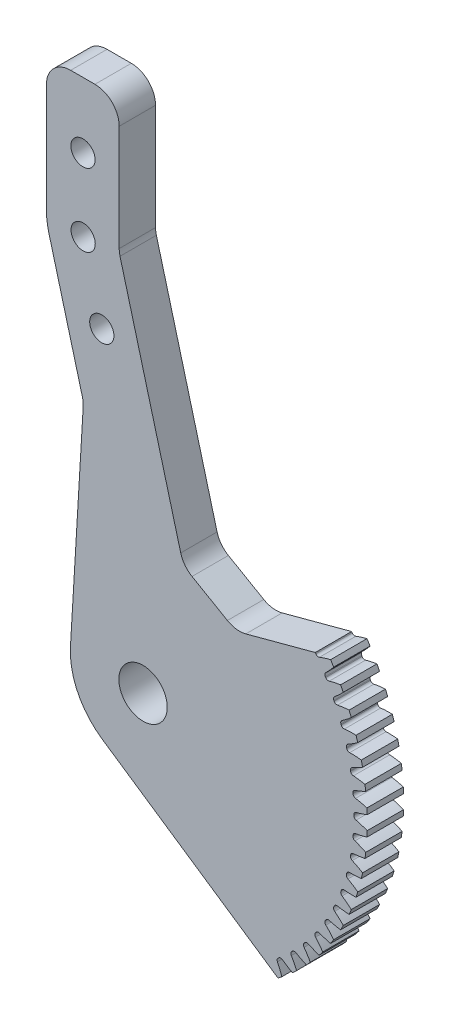
SolidWorks part; units mm, degrees
material "Delrin 2700 NC010, Low Viscosity Acetal Copolymer (SS)"
ref_plane "Front Plane" through (0, 0, 0) normal (0, 0, 1) x (1, 0, 0)
ref_plane "Top Plane" through (0, 0, 0) normal (0, 1, 0) x (1, 0, 0)
ref_plane "Right Plane" through (0, 0, 0) normal (1, 0, 0) x (0, 0, -1)
sketch "Sketch2" plane through (0, 0, 0) normal (0, 0, 1) x (1, 0, 0)
  circle A0 centre (0, 0) radius 60.325
  dimension "D1" = 120.65
extrude "Boss-Extrude2" add sketch "Sketch2" along normal mid plane 9.525
sketch "Sketch3" plane through (0, 0, 4.7625) normal (0, 0, 1) x (1, 0, 0)
  line L0 (0, 0) -> (-57.8242, 215.8028) construction
  line L1 (0, 0) -> (60.325, 0) construction
  line L2 (-15.6133, 58.2695) -> (-24.6525, 92.0044)
  line L3 (-24.6525, 92.0044) -> (-6.2516, 96.9349)
  line L4 (-6.2516, 96.9349) -> (3.5866, 60.2183)
  circle A0 centre (0, 0) radius 60.325 construction
  arc A1 (3.5866, 60.2183) -> (-15.6133, 58.2695) centre (0, 0) ccw
  point P9 (0, 0)
  point P11 (0, 0)
  point P12 (0, 0)
  dimension "D1" = 105
  dimension "D2" = 19.05
  dimension "D3" = 95.25
extrude "Boss-Extrude3" add sketch "Sketch3" against normal up to surface (9.525 mm away) up to face at (60.325, 0, -4.7625)
sketch "Sketch4" plane through (0, 0, 4.7625) normal (0, 0, 1) x (1, 0, 0)
  line L0 (-6.2516, 96.9349) -> (-25.3016, 96.9349)
  line L1 (-25.3016, 96.9349) -> (-25.3016, 131.8599)
  line L2 (-25.3016, 131.8599) -> (-6.2516, 131.8599)
  line L3 (-6.2516, 131.8599) -> (-6.2516, 96.9349)
  line L4 (3.5866, 60.2183) -> (-6.2516, 96.9349) construction
  dimension "D3" = 34.925
  dimension "D1" = 19.05
  dimension "D2" = 165
extrude "Boss-Extrude4" add sketch "Sketch4" against normal up to surface (9.525 mm away) separate body
sketch "Sketch5" plane through (0, 0, 4.7625) normal (0, 0, 1) x (1, 0, 0)
  line L0 (-25.3016, 96.9349) -> (-6.2516, 96.9349) construction
  line L1 (-6.2516, 96.9349) -> (-24.6525, 92.0044) construction
  line L2 (-25.3016, 96.9349) -> (-6.2516, 96.9349)
  line L3 (-6.2516, 96.9349) -> (-24.6525, 92.0044)
  arc A0 (-25.3016, 96.9349) -> (-24.6525, 92.0044) centre (-6.2516, 96.9349) ccw
extrude "Boss-Extrude5" add sketch "Sketch5" against normal up to surface (9.525 mm away)
hole_wizard "1/2 (0.5) Diameter Hole1" positions "Sketch6" profile "Sketch7" hole size "1/2" standard "ANSI Inch" end condition through all
sketch "Sketch6" plane through (0, 0, 4.7625) normal (0, 0, 1) x (1, 0, 0)
  point P0 (0, 0)
sketch "Sketch7" plane through (0, 0, 4.7625) normal (1, 0, 0) x (0, -1, 0)
  line L0 (0, 0) -> (0, 9.525)
  line L1 (0, 9.525) -> (6.3373, 9.525)
  line L2 (6.3373, 9.525) -> (6.3373, 0)
  line L5 (6.3373, 0) -> (0, 0)
  line L11 (0, -6.35) -> (0, 107.95) construction
  dimension "Thru Hole Dia." = 12.6746
  dimension "Thru Hole Depth" = 9.525
sketch "Sketch8" plane through (0, 0, 4.7625) normal (0, 0, 1) x (1, 0, 0)
  line L0 (0, 0) -> (58.2695, 15.6133) construction
  line L1 (-24.6525, 92.0044) -> (-15.6133, 58.2695) construction
  line L2 (24.377, 26.2538) -> (50.3573, 33.2152)
  line L3 (24.377, 26.2538) -> (10.548, 34.2381)
  line L4 (3.5866, 60.2183) -> (10.548, 34.2381)
  line L5 (3.5866, 60.2183) -> (-6.2516, 96.9349) construction
  line L7 (-4.9305, 18.4009) -> (53.339, 34.0141) construction
  arc A0 (-15.6133, 58.2695) -> (3.5866, 60.2183) centre (0, 0) ccw construction
  arc A1 (50.3573, 33.2152) -> (3.5866, 60.2183) centre (0, 0) ccw
  dimension "D2" = 45
  dimension "D3" = 34.925
  dimension "D1" = 19.05
extrude "Cut-Extrude1" cut sketch "Sketch8" against normal through all
sketch "Sketch9" plane through (0, 0, 4.7625) normal (0, 0, 1) x (1, 0, 0)
  line L0 (-15.6133, 58.2695) -> (-19.0163, 1.1326)
  line L1 (0, 0) -> (58.2695, 15.6133) construction
  line L2 (-24.6525, 92.0044) -> (-15.6133, 58.2695) construction
  line L3 (0, 0) -> (36.7235, -47.859) construction
  line L4 (36.7235, -47.859) -> (-10.6778, -15.7761)
  arc A0 (-19.0163, 1.1326) -> (-10.6778, -15.7761) centre (0, 0) ccw
  arc A1 (-15.6133, 58.2695) -> (50.3573, 33.2152) centre (0, 0) ccw construction
  arc A2 (-15.6133, 58.2695) -> (36.7235, -47.859) centre (0, 0) ccw
  dimension "D1" = 38.1
  dimension "D2" = 67.5
extrude "Cut-Extrude2" cut sketch "Sketch9" against normal through all
sketch "Sketch10" plane through (0, 0, 4.7625) normal (0, 0, 1) x (1, 0, 0)
  line L0 (0, 0) -> (60.325, 0) construction
  line L1 (58.6816, -2.5621) -> (0, 0) construction
  circle A0 centre (0, 0) radius 6.3373 construction
  arc A1 (36.7235, -47.859) -> (50.3573, 33.2152) centre (0, 0) ccw construction
  line B0 (23.419, -49.9795) -> (23.233, -50.0662)
  line B1 (18.9739, -51.8304) -> (18.7811, -51.9006)
  line B2 (14.3844, -53.2869) -> (14.1862, -53.34)
  line B3 (13.4521, -57.1763) -> (12.7131, -57.3452)
  line B4 (12.7131, -57.3452) -> (13.7439, -61.9948)
  line B5 (46.8171, 42.9) -> (43.3058, 39.6825)
  line B6 (43.3058, 39.6825) -> (43.8143, 39.1203)
  line B7 (42.2152, 35.5567) -> (42.3471, 35.3995)
  line B8 (45.1535, 31.7421) -> (45.2712, 31.574)
  line B9 (47.7482, 27.6859) -> (47.8508, 27.5082)
  line B10 (49.9795, 23.419) -> (50.0662, 23.233)
  line B11 (51.8304, 18.9739) -> (51.9006, 18.7811)
  line B12 (53.2869, 14.3844) -> (53.34, 14.1862)
  line B13 (54.3378, 9.6854) -> (54.3734, 9.4833)
  line B14 (54.9751, 4.9127) -> (54.993, 4.7083)
  line B15 (55.1941, 0.1026) -> (55.1941, -0.1026)
  line B16 (54.993, -4.7083) -> (54.9751, -4.9127)
  line B17 (54.3734, -9.4833) -> (54.3378, -9.6854)
  line B18 (53.34, -14.1862) -> (53.2869, -14.3844)
  line B19 (51.9006, -18.7811) -> (51.8304, -18.9739)
  line B20 (50.0662, -23.233) -> (49.9795, -23.419)
  line B21 (47.8508, -27.5082) -> (47.7482, -27.6859)
  line B22 (45.2712, -31.574) -> (45.1535, -31.7421)
  line B23 (42.3471, -35.3995) -> (42.2152, -35.5567)
  line B24 (39.1007, -38.9556) -> (38.9556, -39.1007)
  line B25 (35.5567, -42.2152) -> (35.3995, -42.3471)
  line B26 (31.7421, -45.1535) -> (31.574, -45.2712)
  line B27 (27.6859, -47.7482) -> (27.5082, -47.8508)
  circle B28 centre (0, 0) radius 7.9375 construction
  arc B29 (26.4473, -52.4465) -> (27.7921, -51.7464) centre (0, 0) ccw
  arc B30 (24.374, -50.2004) -> (26.4473, -52.4465) centre (42.0357, -35.9774) ccw
  arc B31 (24.374, -50.2004) -> (23.419, -49.9795) centre (23.7558, -50.6982) ccw
  arc B32 (23.233, -50.0662) -> (22.7884, -50.9398) centre (23.5672, -50.7862) ccw
  arc B33 (23.1763, -53.9718) -> (22.7884, -50.9398) centre (0.5402, -55.327) ccw
  arc B34 (21.7757, -54.5519) -> (23.1763, -53.9718) centre (0, 0) ccw
  arc B35 (19.906, -52.1337) -> (21.7757, -54.5519) centre (38.7401, -39.5041) ccw
  arc B36 (19.906, -52.1337) -> (18.9739, -51.8304) centre (19.2468, -52.5758) ccw
  arc B37 (18.7811, -51.9006) -> (18.262, -52.7321) centre (19.0512, -52.647) ccw
  arc B38 (18.3842, -55.7863) -> (18.262, -52.7321) centre (-4.2839, -55.1635) ccw
  arc B39 (16.9383, -56.2422) -> (18.3842, -55.7863) centre (0, 0) ccw
  arc B40 (15.2865, -53.6702) -> (16.9383, -56.2422) centre (35.1497, -42.7302) ccw
  arc B41 (15.2865, -53.6702) -> (14.3844, -53.2869) centre (14.5913, -54.0532) ccw
  arc B42 (14.1862, -53.34) -> (13.5966, -54.1231) centre (14.3902, -54.1071) ccw
  arc B43 (13.4521, -57.1763) -> (13.5966, -54.1231) centre (-9.0754, -54.5803) ccw
  arc B44 (13.7439, -61.9948) -> (46.8171, 42.9) centre (0, 0) ccw
  arc B45 (42.1814, 36.5363) -> (43.8143, 39.1203) centre (23.8718, 49.915) ccw
  arc B46 (42.1814, 36.5363) -> (42.2152, 35.5567) centre (42.8223, 36.068) ccw
  arc B47 (42.3471, 35.3995) -> (43.306, 35.1961) centre (42.9561, 35.9086) ccw
  arc B48 (46.1343, 36.3555) -> (43.306, 35.1961) centre (53.302, 14.8415) ccw
  arc B49 (47.0572, 35.1528) -> (46.1343, 36.3555) centre (0, 0) ccw
  arc B50 (45.2052, 32.7209) -> (47.0572, 35.1528) centre (28.1314, 47.6445) ccw
  arc B51 (45.2052, 32.7209) -> (45.1535, 31.7421) centre (45.8029, 32.1986) ccw
  arc B52 (45.2712, 31.574) -> (46.2087, 31.2878) centre (45.9223, 32.0281) ccw
  arc B53 (49.1273, 32.1963) -> (46.2087, 31.2878) centre (54.3926, 10.1395) ccw
  arc B54 (49.9419, 30.9177) -> (49.1273, 32.1963) centre (0, 0) ccw
  arc B55 (47.885, 28.6565) -> (49.9419, 30.9177) centre (32.1768, 45.0114) ccw
  arc B56 (47.885, 28.6565) -> (47.7482, 27.6859) centre (48.4349, 28.0841) ccw
  arc B57 (47.8508, 27.5082) -> (48.7598, 27.1414) centre (48.5389, 27.9038) ccw
  arc B58 (51.7464, 27.7921) -> (48.7598, 27.1414) centre (55.0694, 5.3602) ccw
  arc B59 (52.4465, 26.4473) -> (51.7464, 27.7921) centre (0, 0) ccw
  arc B60 (50.2004, 24.374) -> (52.4465, 26.4473) centre (35.9774, 42.0357) ccw
  arc B61 (50.2004, 24.374) -> (49.9795, 23.419) centre (50.6982, 23.7558) ccw
  arc B62 (50.0662, 23.233) -> (50.9398, 22.7884) centre (50.7862, 23.5672) ccw
  arc B63 (53.9718, 23.1763) -> (50.9398, 22.7884) centre (55.327, 0.5402) ccw
  arc B64 (54.5519, 21.7757) -> (53.9718, 23.1763) centre (0, 0) ccw
  arc B65 (52.1337, 19.906) -> (54.5519, 21.7757) centre (39.5041, 38.7401) ccw
  arc B66 (52.1337, 19.906) -> (51.8304, 18.9739) centre (52.5758, 19.2468) ccw
  arc B67 (51.9006, 18.7811) -> (52.7321, 18.262) centre (52.647, 19.0512) ccw
  arc B68 (55.7863, 18.3842) -> (52.7321, 18.262) centre (55.1635, -4.2839) ccw
  arc B69 (56.2422, 16.9383) -> (55.7863, 18.3842) centre (0, 0) ccw
  arc B70 (53.6702, 15.2865) -> (56.2422, 16.9383) centre (42.7302, 35.1497) ccw
  arc B71 (53.6702, 15.2865) -> (53.2869, 14.3844) centre (54.0532, 14.5913) ccw
  arc B72 (53.34, 14.1862) -> (54.1231, 13.5966) centre (54.1071, 14.3902) ccw
  arc B73 (57.1763, 13.4521) -> (54.1231, 13.5966) centre (54.5803, -9.0754) ccw
  arc B74 (57.5045, 11.972) -> (57.1763, 13.4521) centre (0, 0) ccw
  arc B75 (54.7983, 10.5507) -> (57.5045, 11.972) centre (45.6311, 31.2917) ccw
  arc B76 (54.7983, 10.5507) -> (54.3378, 9.6854) centre (55.1192, 9.8247) ccw
  arc B77 (54.3734, 9.4833) -> (55.1021, 8.8277) centre (55.1553, 9.6197) ccw
  arc B78 (58.1312, 8.4177) -> (55.1021, 8.8277) centre (53.5816, -13.7979) ccw
  arc B79 (58.3291, 6.9146) -> (58.1312, 8.4177) centre (0, 0) ccw
  arc B80 (55.5093, 5.7346) -> (58.3291, 6.9146) centre (48.1847, 27.1956) ccw
  arc B81 (55.5093, 5.7346) -> (54.9751, 4.9127) centre (55.7657, 4.9834) ccw
  arc B82 (54.993, 4.7083) -> (55.6618, 3.9917) centre (55.7839, 4.776) ccw
  arc B83 (58.6436, 3.3192) -> (55.6618, 3.9917) centre (52.1751, -18.4153) ccw
  arc B84 (58.7098, 1.8046) -> (58.6436, 3.3192) centre (0, 0) ccw
  arc B85 (55.7979, 0.8748) -> (58.7098, 1.8046) centre (50.3716, 22.8926) ccw
  arc B86 (55.7979, 0.8748) -> (55.1941, 0.1026) centre (55.9879, 0.1041) ccw
  arc B87 (55.1941, -0.1026) -> (55.7979, -0.8748) centre (55.9879, -0.1041) ccw
  arc B88 (58.7098, -1.8046) -> (55.7979, -0.8748) centre (50.3716, -22.8926) ccw
  arc B89 (58.6436, -3.3192) -> (58.7098, -1.8046) centre (0, 0) ccw
  arc B90 (55.6618, -3.9917) -> (58.6436, -3.3192) centre (52.1751, 18.4153) ccw
  arc B91 (55.6618, -3.9917) -> (54.993, -4.7083) centre (55.7839, -4.776) ccw
  arc B92 (54.9751, -4.9127) -> (55.5093, -5.7346) centre (55.7657, -4.9834) ccw
  arc B93 (58.3291, -6.9146) -> (55.5093, -5.7346) centre (48.1847, -27.1956) ccw
  arc B94 (58.1312, -8.4177) -> (58.3291, -6.9146) centre (0, 0) ccw
  arc B95 (55.1021, -8.8277) -> (58.1312, -8.4177) centre (53.5816, 13.7979) ccw
  arc B96 (55.1021, -8.8277) -> (54.3734, -9.4833) centre (55.1553, -9.6197) ccw
  arc B97 (54.3378, -9.6854) -> (54.7983, -10.5507) centre (55.1192, -9.8247) ccw
  arc B98 (57.5045, -11.972) -> (54.7983, -10.5507) centre (45.6311, -31.2917) ccw
  arc B99 (57.1763, -13.4521) -> (57.5045, -11.972) centre (0, 0) ccw
  arc B100 (54.1231, -13.5966) -> (57.1763, -13.4521) centre (54.5803, 9.0754) ccw
  arc B101 (54.1231, -13.5966) -> (53.34, -14.1862) centre (54.1071, -14.3902) ccw
  arc B102 (53.2869, -14.3844) -> (53.6702, -15.2865) centre (54.0532, -14.5913) ccw
  arc B103 (56.2422, -16.9383) -> (53.6702, -15.2865) centre (42.7302, -35.1497) ccw
  arc B104 (55.7863, -18.3842) -> (56.2422, -16.9383) centre (0, 0) ccw
  arc B105 (52.7321, -18.262) -> (55.7863, -18.3842) centre (55.1635, 4.2839) ccw
  arc B106 (52.7321, -18.262) -> (51.9006, -18.7811) centre (52.647, -19.0512) ccw
  arc B107 (51.8304, -18.9739) -> (52.1337, -19.906) centre (52.5758, -19.2468) ccw
  arc B108 (54.5519, -21.7757) -> (52.1337, -19.906) centre (39.5041, -38.7401) ccw
  arc B109 (53.9718, -23.1763) -> (54.5519, -21.7757) centre (0, 0) ccw
  arc B110 (50.9398, -22.7884) -> (53.9718, -23.1763) centre (55.327, -0.5402) ccw
  arc B111 (50.9398, -22.7884) -> (50.0662, -23.233) centre (50.7862, -23.5672) ccw
  arc B112 (49.9795, -23.419) -> (50.2004, -24.374) centre (50.6982, -23.7558) ccw
  arc B113 (52.4465, -26.4473) -> (50.2004, -24.374) centre (35.9774, -42.0357) ccw
  arc B114 (51.7464, -27.7921) -> (52.4465, -26.4473) centre (0, 0) ccw
  arc B115 (48.7598, -27.1414) -> (51.7464, -27.7921) centre (55.0694, -5.3602) ccw
  arc B116 (48.7598, -27.1414) -> (47.8508, -27.5082) centre (48.5389, -27.9038) ccw
  arc B117 (47.7482, -27.6859) -> (47.885, -28.6565) centre (48.4349, -28.0841) ccw
  arc B118 (49.9419, -30.9177) -> (47.885, -28.6565) centre (32.1768, -45.0114) ccw
  arc B119 (49.1273, -32.1963) -> (49.9419, -30.9177) centre (0, 0) ccw
  arc B120 (46.2087, -31.2878) -> (49.1273, -32.1963) centre (54.3926, -10.1395) ccw
  arc B121 (46.2087, -31.2878) -> (45.2712, -31.574) centre (45.9223, -32.0281) ccw
  arc B122 (45.1535, -31.7421) -> (45.2052, -32.7209) centre (45.8029, -32.1986) ccw
  arc B123 (47.0572, -35.1528) -> (45.2052, -32.7209) centre (28.1314, -47.6445) ccw
  arc B124 (46.1343, -36.3555) -> (47.0572, -35.1528) centre (0, 0) ccw
  arc B125 (43.306, -35.1961) -> (46.1343, -36.3555) centre (53.302, -14.8415) ccw
  arc B126 (43.306, -35.1961) -> (42.3471, -35.3995) centre (42.9561, -35.9086) ccw
  arc B127 (42.2152, -35.5567) -> (42.1814, -36.5363) centre (42.8223, -36.068) ccw
  arc B128 (43.8143, -39.1203) -> (42.1814, -36.5363) centre (23.8718, -49.915) ccw
  arc B129 (42.7901, -40.238) -> (43.8143, -39.1203) centre (0, 0) ccw
  arc B130 (40.0736, -38.8365) -> (42.7901, -40.238) centre (51.8056, -19.4306) ccw
  arc B131 (40.0736, -38.8365) -> (39.1007, -38.9556) centre (39.663, -39.5158) ccw
  arc B132 (38.9556, -39.1007) -> (38.8365, -40.0736) centre (39.5158, -39.663) ccw
  arc B133 (40.238, -42.7901) -> (38.8365, -40.0736) centre (19.4306, -51.8056) ccw
  arc B134 (39.1203, -43.8143) -> (40.238, -42.7901) centre (0, 0) ccw
  arc B135 (36.5363, -42.1814) -> (39.1203, -43.8143) centre (49.915, -23.8718) ccw
  arc B136 (36.5363, -42.1814) -> (35.5567, -42.2152) centre (36.068, -42.8223) ccw
  arc B137 (35.3995, -42.3471) -> (35.1961, -43.306) centre (35.9086, -42.9561) ccw
  arc B138 (36.3555, -46.1343) -> (35.1961, -43.306) centre (14.8415, -53.302) ccw
  arc B139 (35.1528, -47.0572) -> (36.3555, -46.1343) centre (0, 0) ccw
  arc B140 (32.7209, -45.2052) -> (35.1528, -47.0572) centre (47.6445, -28.1314) ccw
  arc B141 (32.7209, -45.2052) -> (31.7421, -45.1535) centre (32.1986, -45.8029) ccw
  arc B142 (31.574, -45.2712) -> (31.2878, -46.2087) centre (32.0281, -45.9223) ccw
  arc B143 (32.1963, -49.1273) -> (31.2878, -46.2087) centre (10.1395, -54.3926) ccw
  arc B144 (30.9177, -49.9419) -> (32.1963, -49.1273) centre (0, 0) ccw
  arc B145 (28.6565, -47.885) -> (30.9177, -49.9419) centre (45.0114, -32.1768) ccw
  arc B146 (28.6565, -47.885) -> (27.6859, -47.7482) centre (28.0841, -48.4349) ccw
  arc B147 (27.5082, -47.8508) -> (27.1414, -48.7598) centre (27.9038, -48.5389) ccw
  arc B148 (27.7921, -51.7464) -> (27.1414, -48.7598) centre (5.3602, -55.0694) ccw
  dimension "D1" = 2.5
sketch_block_instance "Block1-1"
sketch_block "Block1"
extrude "Cut-Extrude3" cut sketch "Sketch10" against normal blind 12.7
hole_wizard "1/4 (0.25) Diameter Hole1" positions "Sketch11" profile "Sketch12" hole size "1/4" standard "ANSI Inch" end condition through all
sketch "Sketch11" plane through (0, 0, 4.7625) normal (0, 0, 1) x (1, 0, 0)
  line L0 (-15.7766, 131.8599) -> (-15.6951, 95.6917) construction
  line L1 (-6.2516, 131.8599) -> (-25.3016, 131.8599) construction
  line L2 (-15.6951, 95.6917) -> (-6.4128, 60.7347) construction
  line L4 (-25.1387, 94.4484) -> (-6.2516, 96.9349) construction
  line L6 (-15.6133, 58.2695) -> (2.7876, 63.2) construction
  line L7 (10.548, 34.2381) -> (-6.2516, 96.9349) construction
  arc A0 (-25.3016, 96.9349) -> (-24.6525, 92.0044) centre (-6.2516, 96.9349) ccw construction
  point P0 (-15.7381, 114.7417)
  point P2 (-15.6951, 95.6917)
  point P4 (-10.8061, 77.2797)
  dimension "D1" = 19.05
  dimension "D2" = 19.05
sketch "Sketch12" plane through (-15.7381, 114.7417, 4.7625) normal (1, 0, 0) x (0, -1, 0)
  line L0 (0, 0) -> (0, 9.525)
  line L1 (0, 9.525) -> (3.175, 9.525)
  line L2 (3.175, 9.525) -> (3.175, 0)
  line L5 (3.175, 0) -> (0, 0)
  line L11 (0, -6.35) -> (0, 107.95) construction
  dimension "Thru Hole Dia." = 6.35
  dimension "Thru Hole Depth" = 9.525
fillet "Fillet1" radius 6.35 6 edges at (24.377, 26.2538, 0) (10.548, 34.2381, 0) (-6.2516, 96.9349, 0) (-6.2516, 131.8599, 0) (-25.3016, 131.8599, 0) (-15.6133, 58.2695, 0)
sketch "Sketch13" plane through (0, 0, -4.7625) normal (0, 0, 1) x (1, 0, 0)
  line L0 (0, 0) -> (82.2868, 0) construction
  line L1 (25.4, 0) -> (50.8, 0) construction
  line L2 (25.4, 1.6002) -> (50.8, 1.6002)
  line L3 (25.4, -1.6002) -> (50.8, -1.6002)
  arc A0 (25.4, 1.6002) -> (25.4, -1.6002) centre (25.4, 0) ccw
  arc A1 (50.8, -1.6002) -> (50.8, 1.6002) centre (50.8, 0) ccw
  circle A2 centre (0, 0) radius 6.3373 construction
  point P5 (38.1, 0)
  dimension "D1" = 1.6002
  dimension "D3" = 25.4
  dimension "D2" = 25.4
extrude "Cut-Extrude4" cut sketch "Sketch13" along normal blind 1.5875
sketch "Sketch14" plane through (0, 0, -4.7625) normal (0, 0, 1) x (1, 0, 0)
  text T0 "<b>R</b>" font "Century Gothic" height 19.05
  dimension "D1" = 44.45
  dimension "D2" = 6.35
extrude "Cut-Extrude5" cut sketch "Sketch14" along normal blind 1.5875
fillet "Fillet2" radius 0.7937 12 edges at (36.2225, 15.1423, -3.9688) (29.7962, 20.3017, -3.9688) (33.8603, 25.1443, -3.9688) (38.1076, 25.4, -3.9688) (29.5519, 6.35, -3.9688) (39.5654, 23.2019, -3.9687) (39.5654, 17.3366, -3.9687) (42.0077, 25.4, -3.9688) (32.2423, 6.35, -3.9688) (38.9128, 15.1423, -3.9688) (39.5654, 6.35, -3.9688) (42.0077, 6.35, -3.9688)
equation "\"D1@Sketch2\"=2.375*2"
equation "\"D1@Sketch8\"=0.8125in-.015625*4"
equation "\"D2@Sketch11\"=\"D1@Sketch11\""
equation "\"D2@Sketch9\"=80.00deg-2.5-10"
equation "\"D3@Sketch4\"=1.250in+.125"
